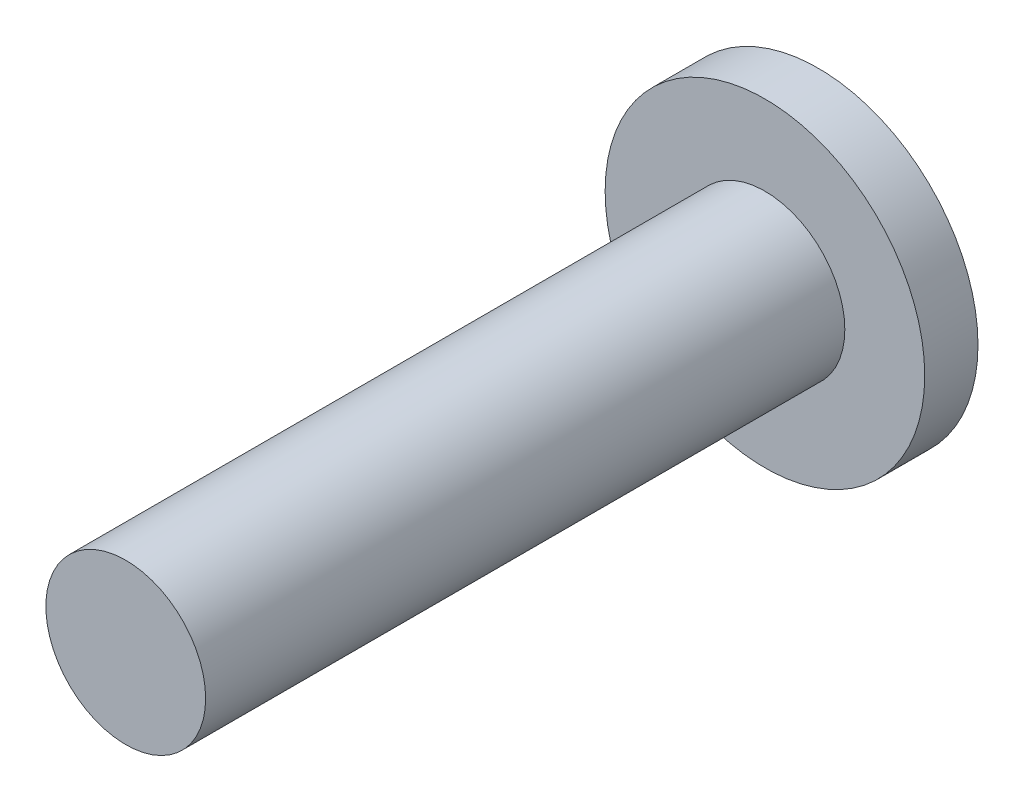
SolidWorks part; units mm, degrees
ref_plane "前视基准面" through (0, 0, 0) normal (0, 0, 1) x (1, 0, 0)
ref_plane "上视基准面" through (0, 0, 0) normal (0, 1, 0) x (1, 0, 0)
ref_plane "右视基准面" through (0, 0, 0) normal (1, 0, 0) x (0, 0, -1)
other "Configuration Table"
sketch "草图1" plane through (0, 0, 0) normal (0, 0, 1) x (1, 0, 0)
  circle A0 centre (0, 0) radius 3
  dimension "D1" = 6
extrude "凸台-拉伸1" add sketch "草图1" along normal blind 1
sketch "草图2" plane through (0, 0, 0) normal (0, 0, -1) x (-1, 0, 0)
  line L1 (1.1547, 0) -> (0.5774, 1)
  line L2 (0.5774, 1) -> (-0.5774, 1)
  line L3 (-0.5774, 1) -> (-1.1547, 0)
  line L4 (-1.1547, 0) -> (-0.5774, -1)
  line L5 (-0.5774, -1) -> (0.5774, -1)
  line L6 (0.5774, -1) -> (1.1547, 0)
  circle A0 centre (0, 0) radius 1 construction
  dimension "D1" = 2
extrude "切除-拉伸1" cut sketch "草图2" against normal blind 1
sketch "草图3" plane through (0, 0, 1) normal (0, 0, 1) x (1, 0, 0)
  circle A0 centre (0, 0) radius 1.5
  dimension "D1" = 3
extrude "凸台-拉伸2" add sketch "草图3" along normal blind 12
